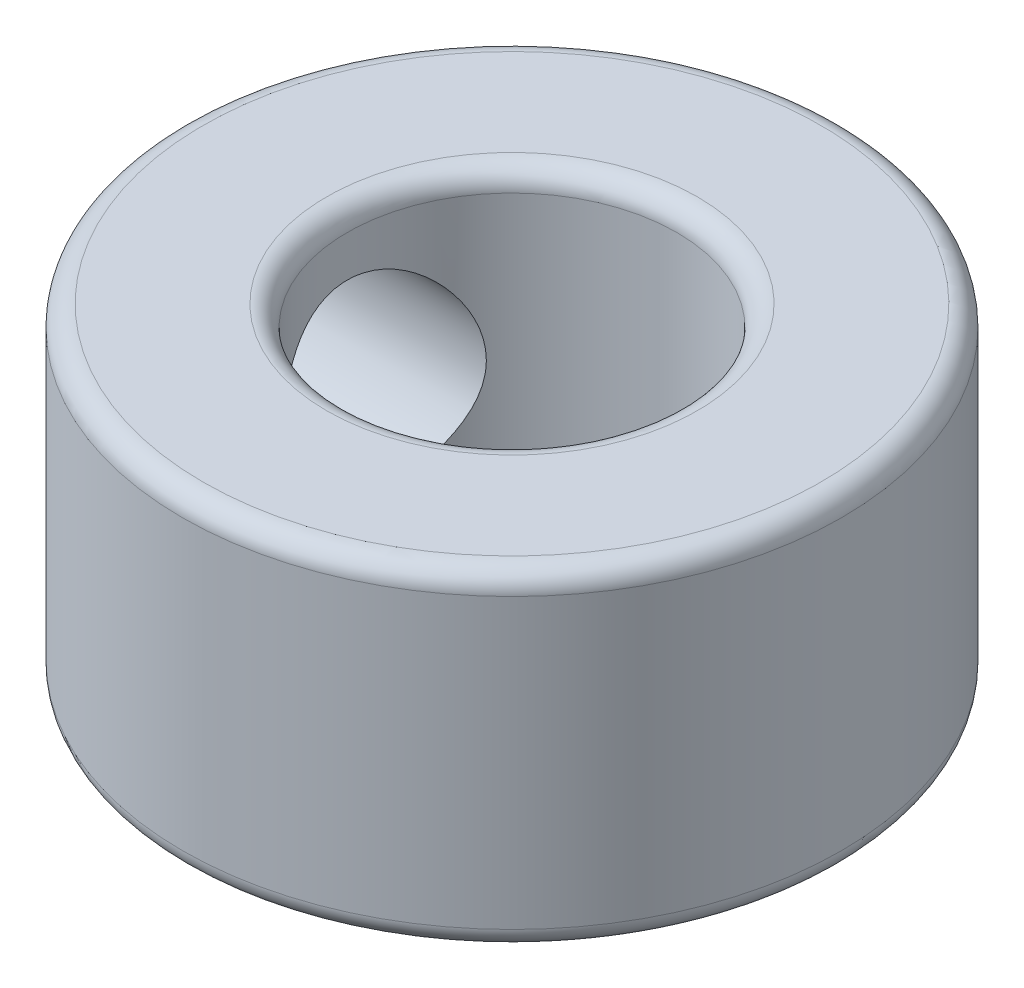
SolidWorks part; units mm, degrees
ref_plane "Front Plane" through (0, 0, 0) normal (0, 0, 1) x (1, 0, 0)
ref_plane "Top Plane" through (0, 0, 0) normal (0, 1, 0) x (1, 0, 0)
ref_plane "Right Plane" through (0, 0, 0) normal (1, 0, 0) x (0, 0, -1)
sketch "Sketch1" plane through (0, 0, 0) normal (0, 1, 0) x (1, 0, 0)
  circle A0 centre (0, 0) radius 8
  circle A1 centre (0, 0) radius 4
  dimension "D1" = 16
  dimension "D2" = 8
extrude "Boss-Extrude1" add sketch "Sketch1" along normal blind 8
sketch "Sketch4" plane through (0, 0, 0) normal (1, 0, 0) x (0, 0, -1)
  line L0 (0, 0) -> (0, 4) construction
  circle A0 centre (0, 4) radius 2.5
  dimension "D2" = 5
  dimension "D1" = 4
extrude "Cut-Extrude1" cut sketch "Sketch4" against normal blind 8
fillet "Fillet1" radius 0.5 4 edges at (0, 0, 4) (0, 8, 4) (0, 0, 8) (0, 8, 8)
